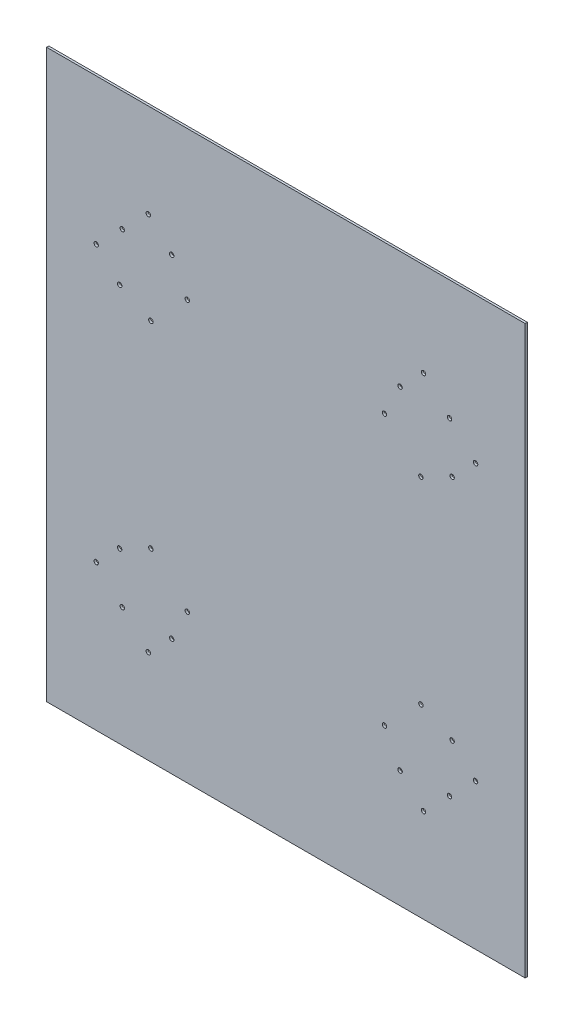
SolidWorks part; units mm, degrees
ref_plane "Front Plane" through (0, 0, 0) normal (0, 0, 1) x (1, 0, 0)
ref_plane "Top Plane" through (0, 0, 0) normal (0, 1, 0) x (1, 0, 0)
ref_plane "Right Plane" through (0, 0, 0) normal (1, 0, 0) x (0, 0, -1)
sketch "Sketch1" plane through (0, 0, 0) normal (0, 0, 1) x (1, 0, 0)
  line L4 (740.7773, -1889.2272) -> (1390.7773, -1889.2272)
  line L5 (1390.7773, -1889.2272) -> (1390.7773, -1119.2272)
  line L6 (1390.7773, -1119.2272) -> (740.7773, -1119.2272)
  line L7 (740.7773, -1119.2272) -> (740.7773, -1889.2272)
  line L12 (740.7773, -1889.2272) -> (1390.7773, -1889.2272)
  line L13 (1390.7773, -1889.2272) -> (1390.7773, -1119.2272)
  line L14 (1390.7773, -1119.2272) -> (740.7773, -1119.2272)
  line L15 (740.7773, -1119.2272) -> (740.7773, -1889.2272)
  circle A1 centre (1288.0916, -1281.9129) radius 3
  circle A2 centre (1288.0916, -1281.9129) radius 3
  circle A3 centre (843.4629, -1726.5416) radius 3
  circle A4 centre (843.4629, -1726.5416) radius 3
  circle A5 centre (931.8512, -1687.6507) radius 3
  circle A6 centre (931.8512, -1687.6507) radius 3
  circle A7 centre (910.638, -1730.0771) radius 3
  circle A8 centre (910.638, -1730.0771) radius 3
  circle A9 centre (878.8182, -1761.8969) radius 3
  circle A10 centre (878.8182, -1761.8969) radius 3
  circle A11 centre (1323.447, -1317.2682) radius 3
  circle A12 centre (1323.447, -1317.2682) radius 3
  circle A13 centre (1249.2008, -1370.3012) radius 3
  circle A14 centre (1249.2008, -1370.3012) radius 3
  circle A15 centre (1291.6272, -1349.088) radius 3
  circle A16 centre (1291.6272, -1349.088) radius 3
  circle A17 centre (1220.9165, -1278.3773) radius 3
  circle A18 centre (1220.9165, -1278.3773) radius 3
  circle A19 centre (1199.7033, -1320.8037) radius 3
  circle A20 centre (1199.7033, -1320.8037) radius 3
  circle A21 centre (1252.7363, -1246.5575) radius 3
  circle A22 centre (1252.7363, -1246.5575) radius 3
  circle A23 centre (882.3538, -1638.1533) radius 3
  circle A24 centre (882.3538, -1638.1533) radius 3
  circle A25 centre (808.1076, -1691.1863) radius 3
  circle A26 centre (808.1076, -1691.1863) radius 3
  circle A27 centre (839.9274, -1659.3665) radius 3
  circle A28 centre (839.9274, -1659.3665) radius 3
  circle A29 centre (1291.6272, -1659.3665) radius 3
  circle A30 centre (1291.6272, -1659.3665) radius 3
  circle A31 centre (1323.447, -1691.1863) radius 3
  circle A32 centre (1323.447, -1691.1863) radius 3
  circle A33 centre (1288.0916, -1726.5416) radius 3
  circle A34 centre (1288.0916, -1726.5416) radius 3
  circle A35 centre (1252.7363, -1761.8969) radius 3
  circle A36 centre (1252.7363, -1761.8969) radius 3
  circle A37 centre (1220.9165, -1730.0771) radius 3
  circle A38 centre (1220.9165, -1730.0771) radius 3
  circle A39 centre (1199.7033, -1687.6507) radius 3
  circle A40 centre (1199.7033, -1687.6507) radius 3
  circle A41 centre (1249.2008, -1638.1533) radius 3
  circle A42 centre (1249.2008, -1638.1533) radius 3
  circle A43 centre (839.9274, -1349.088) radius 3
  circle A44 centre (839.9274, -1349.088) radius 3
  circle A45 centre (808.1076, -1317.2682) radius 3
  circle A46 centre (808.1076, -1317.2682) radius 3
  circle A47 centre (843.4629, -1281.9129) radius 3
  circle A48 centre (843.4629, -1281.9129) radius 3
  circle A49 centre (878.8182, -1246.5575) radius 3
  circle A50 centre (878.8182, -1246.5575) radius 3
  circle A51 centre (910.638, -1278.3773) radius 3
  circle A52 centre (910.638, -1278.3773) radius 3
  circle A53 centre (931.8512, -1320.8037) radius 3
  circle A54 centre (931.8512, -1320.8037) radius 3
  circle A55 centre (882.3538, -1370.3012) radius 3
  circle A56 centre (882.3538, -1370.3012) radius 3
  dimension "D1" = 0
  dimension "D2" = 0
  dimension "D3" = 0
  dimension "D4" = 0
  dimension "D5" = 0
  dimension "D6" = 0
  dimension "D7" = 0
  dimension "D8" = 0
  dimension "D9" = 0
  dimension "D10" = 0
  dimension "D11" = 0
  dimension "D12" = 0
  dimension "D13" = 0
  dimension "D14" = 0
  dimension "D15" = 0
  dimension "D16" = 0
  dimension "D17" = 0
  dimension "D18" = 0
  dimension "D19" = 0
  dimension "D20" = 0
  dimension "D21" = 0
  dimension "D22" = 0
  dimension "D23" = 0
  dimension "D24" = 0
  dimension "D25" = 0
  dimension "D26" = 0
  dimension "D27" = 0
  dimension "D28" = 0
  dimension "D29" = 0
extrude "Boss-Extrude2" add sketch "Sketch1" along normal blind 3
